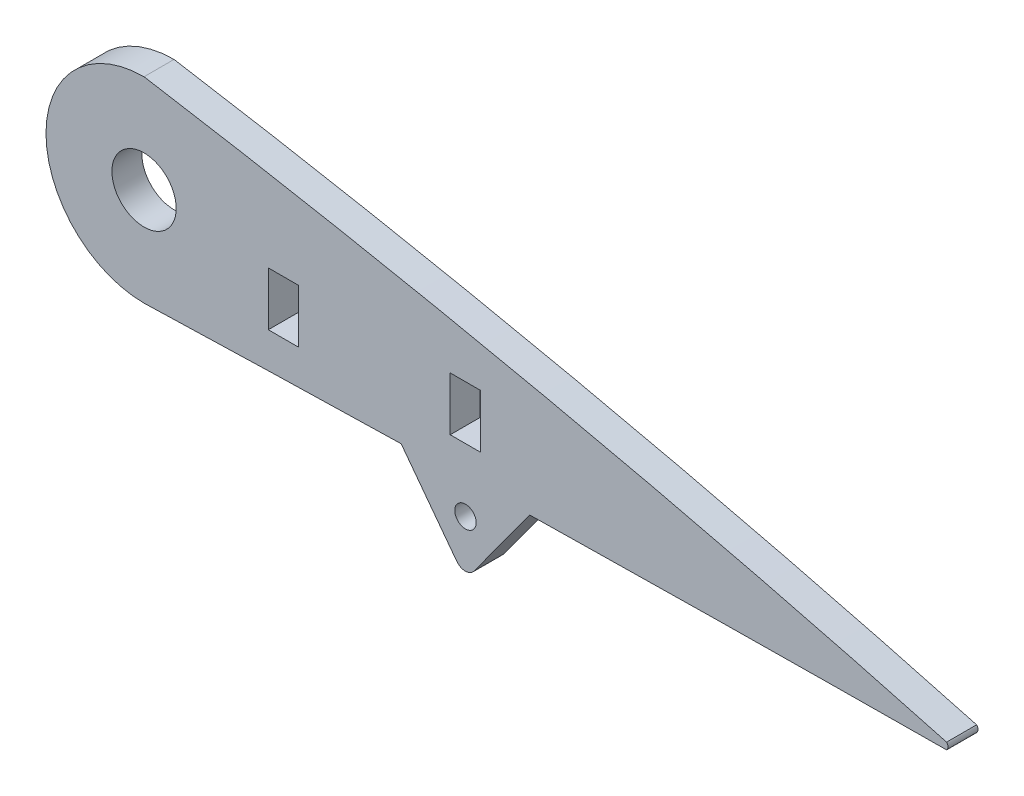
SolidWorks part; units mm, degrees
material "Фанера"
ref_plane "Front Plane" through (0, 0, 0) normal (0, 0, 1) x (1, 0, 0)
ref_plane "Top Plane" through (0, 0, 0) normal (0, 1, 0) x (1, 0, 0)
ref_plane "Right Plane" through (0, 0, 0) normal (1, 0, 0) x (0, 0, -1)
curve "Кривая5"
  spline degree 3 poles (0.048, 0.6214, 0) (0.0227, 0.3735, 0) (-0.0278, -0.1225, 0) (0.078, -0.8844, 0) (0.3497, -1.6388, 0) (0.8143, -2.3651, 0) (1.4635, -3.0393, 0) (2.291, -3.661, 0) (3.3059, -4.2358, 0) (4.5353, -4.7737, 0) (6.0297, -5.2822, 0) (7.869, -5.7653, 0) (10.1688, -6.2217, 0) (13.0754, -6.6396, 0) (16.7281, -6.993, 0) (21.19, -7.2473, 0) (26.4, -7.3766, 0) (32.1974, -7.3763, 0) (38.3978, -7.2614, 0) (44.8576, -7.0566, 0) (51.4865, -6.7865, 0) (58.231, -6.4723, 0) (65.0521, -6.1329, 0) (71.9108, -5.784, 0) (78.7714, -5.4397, 0) (85.6105, -5.111, 0) (92.4321, -4.805, 0) (99.255, -4.532, 0) (106.0974, -4.2783, 0) (112.9692, -4.0031, 0) (119.8644, -3.7232, 0) (126.7739, -3.4401, 0) (133.6816, -3.1587, 0) (140.5819, -2.8824, 0) (147.472, -2.6139, 0) (154.3526, -2.3556, 0) (161.225, -2.1094, 0) (168.0909, -1.8766, 0) (174.9516, -1.6586, 0) (181.8086, -1.4564, 0) (188.6632, -1.2704, 0) (195.5166, -1.1011, 0) (202.3695, -0.9486, 0) (209.2212, -0.8129, 0) (216.0668, -0.6936, 0) (222.8864, -0.5903, 0) (229.6176, -0.5029, 0) (236.0874, -0.4315, 0) (241.9808, -0.3765, 0) (246.559, -0.3395, 0) (249.1205, -0.3213, 0) (250, -0.315, 0) knots 0 0 0 0 0.002941 0.005884 0.009016 0.012365 0.016008 0.020037 0.024574 0.029784 0.035897 0.04324 0.052276 0.063635 0.077983 0.095698 0.11652 0.139661 0.164312 0.189919 0.216157 0.242838 0.269834 0.296993 0.324123 0.351139 0.378036 0.404946 0.431961 0.459078 0.486347 0.513641 0.540929 0.568176 0.59538 0.622543 0.649673 0.676775 0.703855 0.730919 0.757971 0.785018 0.812062 0.839103 0.866132 0.893099 0.919831 0.94581 0.969681 0.98959 1 1 1 1
curve "Кривая6"
  spline degree 3 poles (250, 0.315, 0) (249.1557, 0.545, 0) (246.7202, 1.2085, 0) (242.3913, 2.3583, 0) (236.8498, 3.7876, 0) (230.7799, 5.298, 0) (224.4559, 6.8129, 0) (218.0305, 8.2916, 0) (211.5624, 9.7197, 0) (205.0724, 11.0924, 0) (198.568, 12.4079, 0) (192.0524, 13.6653, 0) (185.5276, 14.8641, 0) (178.9953, 16.0034, 0) (172.4571, 17.0824, 0) (165.9143, 18.0998, 0) (159.3687, 19.0545, 0) (152.8218, 19.9449, 0) (146.2754, 20.7693, 0) (139.7314, 21.5257, 0) (133.1918, 22.212, 0) (126.6587, 22.8257, 0) (120.1368, 23.364, 0) (113.6286, 23.8247, 0) (107.1527, 24.2002, 0) (100.7411, 24.4984, 0) (94.4118, 24.6866, 0) (88.1559, 24.7401, 0) (81.949, 24.6588, 0) (75.7805, 24.441, 0) (69.6537, 24.0819, 0) (63.5754, 23.578, 0) (57.5552, 22.9249, 0) (51.6058, 22.1191, 0) (45.7444, 21.1566, 0) (39.9959, 20.0354, 0) (34.3979, 18.7563, 0) (29.0104, 17.3276, 0) (23.9258, 15.7719, 0) (19.2707, 14.1343, 0) (15.1791, 12.4833, 0) (11.7405, 10.8956, 0) (8.9594, 9.4296, 0) (6.7609, 8.1086, 0) (5.0337, 6.9246, 0) (3.6717, 5.8542, 0) (2.5921, 4.8713, 0) (1.7382, 3.9526, 0) (1.0699, 3.0809, 0) (0.5716, 2.2416, 0) (0.2158, 1.4308, 0) (0.1023, 0.8832, 0) (0.048, 0.6214, 0) knots 0 0 0 0 0.010162 0.029313 0.052012 0.076619 0.101948 0.127526 0.153184 0.178868 0.204558 0.230246 0.255926 0.281594 0.307246 0.332878 0.358485 0.384061 0.409603 0.435104 0.460559 0.485959 0.511303 0.536552 0.561723 0.586629 0.611085 0.635251 0.659272 0.683164 0.706922 0.730536 0.753983 0.777235 0.800246 0.822951 0.845237 0.866916 0.887662 0.906968 0.924203 0.938879 0.950932 0.960693 0.968647 0.975233 0.980795 0.985584 0.989782 0.993521 0.996902 1 1 1 1
sketch "Эскиз1" plane through (0, 0, 0) normal (0, 0, 1) x (1, 0, 0)
  line L0 (250.1305, 0) -> (250.1305, 54.8427) construction
  line L1 (0, 0) -> (0, 70.5199) construction
  line L2 (0, 0) -> (253.0634, 0) construction
  line L3 (62.5326, 62.6361) -> (62.5326, -41.5636) construction
  line L4 (142.5326, 67.9319) -> (142.5326, -57.0034) construction
  line L5 (175.0913, 63.8571) -> (175.0913, -32.3947) construction
  line L6 (32.5326, -14.3434) -> (32.5326, 29.5903) construction
  line L7 (165.9405, 18.0854) -> (165.9405, -1.9504)
  line L8 (199.0913, -1.0223) -> (204.28, -7.9265)
  line L9 (203.6663, 6.9939) -> (206.5163, 6.9939)
  line L10 (203.6663, 6.9939) -> (203.6663, 1.9939)
  line L11 (203.6663, 1.9939) -> (206.5163, 1.9939)
  line L12 (206.5163, 6.9939) -> (206.5163, 1.9939)
  line L13 (203.6663, 6.9939) -> (206.5163, 1.9939) construction
  line L14 (203.6663, 1.9939) -> (206.5163, 6.9939) construction
  line L15 (205.8873, -7.915) -> (211.0913, -0.7814)
  line L16 (205.0913, 14.1754) -> (205.0913, -11.6971) construction
  line L17 (205.0913, 4.4939) -> (182.6192, 4.4939) construction
  line L19 (186.6913, 1.9939) -> (189.4913, 1.9939)
  line L20 (186.6913, 1.9939) -> (186.6913, 6.9939)
  line L21 (186.6913, 6.9939) -> (189.4913, 6.9939)
  line L22 (189.4913, 1.9939) -> (189.4913, 6.9939)
  line L23 (186.6913, 1.9939) -> (189.4913, 6.9939) construction
  line L24 (186.6913, 6.9939) -> (189.4913, 1.9939) construction
  arc A0 (250, 0.315) -> (250, -0.315) centre (249.685, 0) cw
  circle A1 centre (62.5326, 8.5962) radius 8.1
  circle A2 centre (142.5326, 8.5962) radius 5.1
  circle A3 centre (32.5326, 5.4481) radius 7
  circle A5 centre (102.5326, 8.5962) radius 9.5
  arc A6 (175.0913, -1.657) -> (175.0913, 16.6448) centre (175.0913, 7.4939) cw
  circle A7 centre (175.0913, 7.4939) radius 3
  arc A8 (204.28, -7.9265) -> (205.8873, -7.915) centre (205.0794, -7.3257) ccw
  circle A9 centre (205.0913, -3.9061) radius 1
  spline S0 degree 3 poles (0.048, 0.6214) (0.0227, 0.3735) (-0.0278, -0.1225) (0.078, -0.8844) (0.3497, -1.6388) (0.8143, -2.3651) (1.4635, -3.0393) (2.291, -3.661) (3.3059, -4.2358) (4.5353, -4.7737) (6.0297, -5.2822) (7.869, -5.7653) (10.1688, -6.2217) (13.0754, -6.6396) (16.7281, -6.993) (21.19, -7.2473) (26.4, -7.3766) (32.1974, -7.3763) (38.3978, -7.2614) (44.8576, -7.0566) (51.4865, -6.7865) (58.231, -6.4723) (65.0521, -6.1329) (71.9108, -5.784) (78.7714, -5.4397) (85.6105, -5.111) (92.4321, -4.805) (99.255, -4.532) (106.0974, -4.2783) (112.9692, -4.0031) (119.8644, -3.7232) (126.7739, -3.4401) (133.6816, -3.1587) (140.5819, -2.8824) (147.472, -2.6139) (154.3526, -2.3556) (161.225, -2.1094) (168.0909, -1.8766) (174.9516, -1.6586) (181.8086, -1.4564) (188.6632, -1.2704) (195.5166, -1.1011) (202.3695, -0.9486) (211.4992, -0.7677) (220.6031, -0.6199) (229.6176, -0.5029) (236.0874, -0.4315) (241.9808, -0.3765) (246.559, -0.3395) (249.1205, -0.3213) (250, -0.315) knots 0 0 0 0 0.002941 0.005884 0.009016 0.012365 0.016008 0.020037 0.024574 0.029784 0.035897 0.04324 0.052276 0.063635 0.077983 0.095698 0.11652 0.139661 0.164312 0.189919 0.216157 0.242838 0.269834 0.296993 0.324123 0.351139 0.378036 0.404946 0.431961 0.459078 0.486347 0.513641 0.540929 0.568176 0.59538 0.622543 0.649673 0.676775 0.703855 0.730919 0.757971 0.785018 0.812062 0.839103 0.893099 0.919831 0.94581 0.969681 0.98959 1 1 1 1 construction
  spline S1 degree 3 poles (1021.8633, 1838.7787) (414.3615, -64.7736) (332.0293, -21.4512) (242.3913, 2.3583) (236.8498, 3.7876) (230.7799, 5.298) (224.4559, 6.8129) (218.0305, 8.2916) (211.5624, 9.7197) (205.0724, 11.0924) (198.568, 12.4079) (192.0524, 13.6653) (185.5276, 14.8641) (178.9953, 16.0034) (172.4571, 17.0824) (165.9143, 18.0998) (159.3687, 19.0545) (152.8218, 19.9449) (146.2754, 20.7693) (139.7314, 21.5257) (133.1918, 22.212) (126.6587, 22.8257) (120.1368, 23.364) (113.6286, 23.8247) (107.1527, 24.2002) (100.7411, 24.4984) (94.4118, 24.6866) (88.1559, 24.7401) (81.949, 24.6588) (75.7805, 24.441) (69.6537, 24.0819) (63.5754, 23.578) (57.5552, 22.9249) (51.6058, 22.1191) (45.7444, 21.1566) (39.9959, 20.0354) (34.3979, 18.7563) (29.0104, 17.3276) (23.9258, 15.7719) (19.2707, 14.1343) (15.1791, 12.4833) (11.7405, 10.8956) (8.9594, 9.4296) (6.7609, 8.1086) (5.0337, 6.9246) (3.6717, 5.8542) (2.5921, 4.8713) (1.7382, 3.9526) (1.0699, 3.0809) (0.5716, 2.2416) (-4.3308, -8.9285) (41.0506, -34.7699) (-1925.2597, 540.0689) knots -1.025 -1.025 -1.025 -1.025 0.010162 0.029313 0.052012 0.076619 0.101948 0.127526 0.153184 0.178868 0.204558 0.230246 0.255926 0.281594 0.307246 0.332878 0.358485 0.384061 0.409603 0.435104 0.460559 0.485959 0.511303 0.536552 0.561723 0.586629 0.611085 0.635251 0.659272 0.683164 0.706922 0.730536 0.753983 0.777235 0.800246 0.822951 0.845237 0.866916 0.887662 0.906968 0.924203 0.938879 0.950932 0.960693 0.968647 0.975233 0.980795 0.985584 0.989782 0.993521 0.996902 1.130551 1.130551 1.130551 1.130551 only from (250, 0.315) to (0.048, 0.6214) construction
  spline S2 degree 3 poles (0.048, 0.6214) (0.0227, 0.3735) (-0.0278, -0.1225) (0.078, -0.8844) (0.3497, -1.6388) (0.8143, -2.3651) (1.4635, -3.0393) (2.291, -3.661) (3.3059, -4.2358) (4.5353, -4.7737) (6.0297, -5.2822) (7.869, -5.7653) (10.1688, -6.2217) (13.0754, -6.6396) (16.7281, -6.993) (21.19, -7.2473) (26.4, -7.3766) (32.1974, -7.3763) (38.3978, -7.2614) (44.8576, -7.0566) (51.4865, -6.7865) (58.231, -6.4723) (65.0521, -6.1329) (71.9108, -5.784) (78.7714, -5.4397) (85.6105, -5.111) (92.4321, -4.805) (99.255, -4.532) (106.0974, -4.2783) (112.9692, -4.0031) (119.8644, -3.7232) (126.7739, -3.4401) (133.6816, -3.1587) (140.5819, -2.8824) (147.472, -2.6139) (154.3526, -2.3556) (161.225, -2.1094) (168.0909, -1.8766) (174.9516, -1.6586) (181.8086, -1.4564) (188.6632, -1.2704) (194.4239, -1.1281) (197.8998, -1.0487) (199.0913, -1.0223) knots 0 0 0 0 0.002941 0.005884 0.009016 0.012365 0.016008 0.020037 0.024574 0.029784 0.035897 0.04324 0.052276 0.063635 0.077983 0.095698 0.11652 0.139661 0.164312 0.189919 0.216157 0.242838 0.269834 0.296993 0.324123 0.351139 0.378036 0.404946 0.431961 0.459078 0.486347 0.513641 0.540929 0.568176 0.59538 0.622543 0.649673 0.676775 0.703855 0.730919 0.757971 0.785018 0.799124 0.799124 0.799124 0.799124
  spline S3 degree 3 poles (250, 0.315) (249.1557, 0.545) (246.7202, 1.2085) (242.3913, 2.3583) (236.8498, 3.7876) (230.7799, 5.298) (224.4559, 6.8129) (218.0305, 8.2916) (211.5624, 9.7197) (205.0724, 11.0924) (198.568, 12.4079) (192.0524, 13.6653) (185.5276, 14.8641) (178.9953, 16.0034) (172.4571, 17.0824) (165.9143, 18.0998) (159.3687, 19.0545) (152.8218, 19.9449) (146.2754, 20.7693) (139.7314, 21.5257) (133.1918, 22.212) (126.6587, 22.8257) (120.1368, 23.364) (113.6286, 23.8247) (107.1527, 24.2002) (100.7411, 24.4984) (94.4118, 24.6866) (88.1559, 24.7401) (81.949, 24.6588) (75.7805, 24.441) (69.6537, 24.0819) (63.5754, 23.578) (57.5552, 22.9249) (51.6058, 22.1191) (45.7444, 21.1566) (39.9959, 20.0354) (34.3979, 18.7563) (29.0104, 17.3276) (23.9258, 15.7719) (19.2707, 14.1343) (15.1791, 12.4833) (11.7405, 10.8956) (8.9594, 9.4296) (6.7609, 8.1086) (5.0337, 6.9246) (3.6717, 5.8542) (2.5921, 4.8713) (1.7382, 3.9526) (1.0699, 3.0809) (0.5716, 2.2416) (0.2158, 1.4308) (0.1023, 0.8832) (0.048, 0.6214) knots 0 0 0 0 0.010162 0.029313 0.052012 0.076619 0.101948 0.127526 0.153184 0.178868 0.204558 0.230246 0.255926 0.281594 0.307246 0.332878 0.358485 0.384061 0.409603 0.435104 0.460559 0.485959 0.511303 0.536552 0.561723 0.586629 0.611085 0.635251 0.659272 0.683164 0.706922 0.730536 0.753983 0.777235 0.800246 0.822951 0.845237 0.866916 0.887662 0.906968 0.924203 0.938879 0.950932 0.960693 0.968647 0.975233 0.980795 0.985584 0.989782 0.993521 0.996902 1 1 1 1
  spline S4 degree 3 poles (211.0913, -0.7814) (215.0296, -0.7106) (221.2261, -0.6119) (229.6176, -0.5029) (236.0874, -0.4315) (241.9808, -0.3765) (246.559, -0.3395) (249.1205, -0.3213) (250, -0.315) knots 0.846478 0.846478 0.846478 0.846478 0.893099 0.919831 0.94581 0.969681 0.98959 1 1 1 1
  point P22 (62.5326, 23.4501)
  point P23 (62.5326, -6.2577)
  point P26 (32.5326, 18.2506)
  point P27 (32.5326, -7.3543)
  point P30 (175.0913, 16.6448)
  point P31 (175.0913, -1.657)
  point P37 (205.0913, 4.4939)
  point P51 (205.0913, -9.0061)
  point P55 (188.0913, 4.4939)
  dimension "D3" = 16.2
  dimension "D8" = 14
  dimension "D10" = 10.2
  dimension "D9" = 19
  dimension "D15" = 9.1509
  dimension "D16" = 6
  dimension "D24" = 1
  dimension "D25" = 2
  dimension "D1" = 250.1305
  dimension "D2" = 62.5326
  dimension "D4" = 80
  dimension "D5" = 75.0391
  dimension "D6" = 29.7079
  dimension "D7" = 14.8539
  dimension "D11" = 40
  dimension "D12" = 30
  dimension "D13" = 25.6049
  dimension "D14" = 12.8025
  dimension "D17" = 2.85
  dimension "D18" = 5
  dimension "D19" = 30
  dimension "D20" = 3
  dimension "D21" = 6
  dimension "D22" = 6
  dimension "D23" = 13.5
  dimension "D26" = 8.4
  dimension "D27" = 2.8
  dimension "D28" = 5
  dimension "D29" = 17
extrude "Бобышка-Вытянуть1" add sketch "Эскиз1" along normal mid plane 2.8 contours A0 S3 A6 S2 A7
equation "\"D2@Эскиз1\"=\"D1@Эскиз1\"/4"
equation "\"D7@Эскиз1\"=\"D6@Эскиз1\"/2"
equation "\"D5@Эскиз1\"=\"D1@Эскиз1\"*0.3"
equation "\"D14@Эскиз1\"=\"D13@Эскиз1\"/2"
equation "\"t\"= 2.85"
